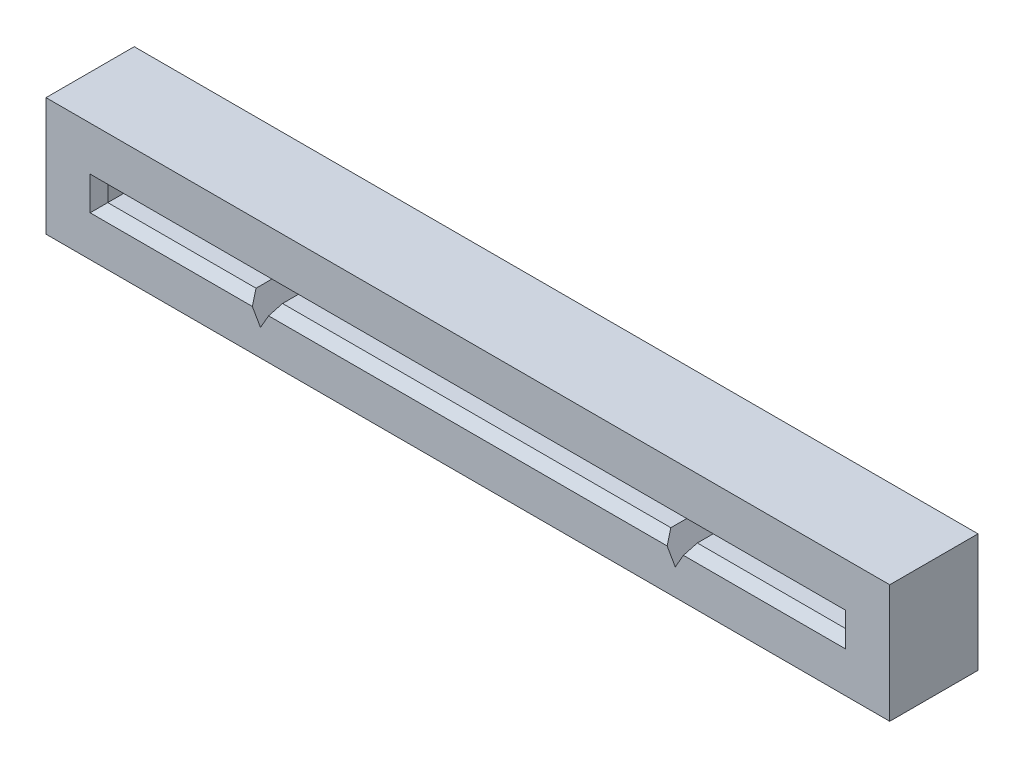
SolidWorks part; units mm, degrees
material "Сосна"
ref_plane "Front" through (0, 0, 0) normal (0, 0, 1) x (1, 0, 0)
ref_plane "Top" through (0, 0, 0) normal (0, 1, 0) x (1, 0, 0)
ref_plane "Right" through (0, 0, 0) normal (1, 0, 0) x (0, 0, -1)
sketch "Эскиз1" plane through (0, 66.7543, 0) normal (0, 0, 1) x (-1, 0, 0)
  line L1 (23.9, 63.3043) -> (-23.9, 70.0043) construction
  line L4 (-20.9, 67.2043) -> (-20.9, 66.3043)
  line L5 (-20.9, 66.3043) -> (20.9, 66.3043)
  line L6 (20.9, 67.2043) -> (20.9, 66.3043)
  line L7 (-20.9, 67.2043) -> (20.9, 66.3043) construction
  line L8 (-20.9, 66.3043) -> (20.9, 67.2043) construction
  line L22 (20.9, 67.2043) -> (-20.9, 67.2043) construction
  line L23 (0, 66.3043) -> (0, 67.2043) construction
  line L24 (-20.9, 67.2043) -> (-12.5, 67.2043)
  line L25 (-12.5, 67.2043) -> (-11.75, 68.5043)
  line L26 (-11.75, 68.5043) -> (-11, 67.2043)
  line L27 (-11, 67.2043) -> (11, 67.2043)
  line L28 (11, 67.2043) -> (11.75, 68.5043)
  line L29 (11.75, 68.5043) -> (12.5, 67.2043)
  line L30 (12.5, 67.2043) -> (20.9, 67.2043)
  line L31 (-23.9, 63.3043) -> (23.9, 63.3043)
  line L32 (-23.9, 63.3043) -> (-23.9, 70.0043)
  line L33 (-23.9, 70.0043) -> (23.9, 70.0043)
  line L34 (23.9, 63.3043) -> (23.9, 70.0043)
  line L35 (-23.9, 63.3043) -> (23.9, 70.0043) construction
  point P6 (0, 66.7543)
  point P12 (0, 66.7543)
  point P14 (0, 67.2043)
  point P15 (0, 66.7543)
  point P22 (0, 66.7543)
  point P26 (0, 66.6543)
  dimension "D1" = 41.8
  dimension "D2" = 0.9
  dimension "D3" = 1.3
  dimension "D4" = 23.5
  dimension "D5" = 1.5
  dimension "D6" = 3
  dimension "D7" = 3
  dimension "1" = 1.5
extrude "Бобышка-Вытянуть1" add sketch "Эскиз1" along normal blind 5
chamfer "Фаска1" distance 0.5 angle 45 6 edges at (0, -0.45, 5) (-16.7, -0.45, 5) (-20.9, 0, 5) (16.7, -0.45, 5) (20.9, 0, 5) (0, 0.45, 5)
